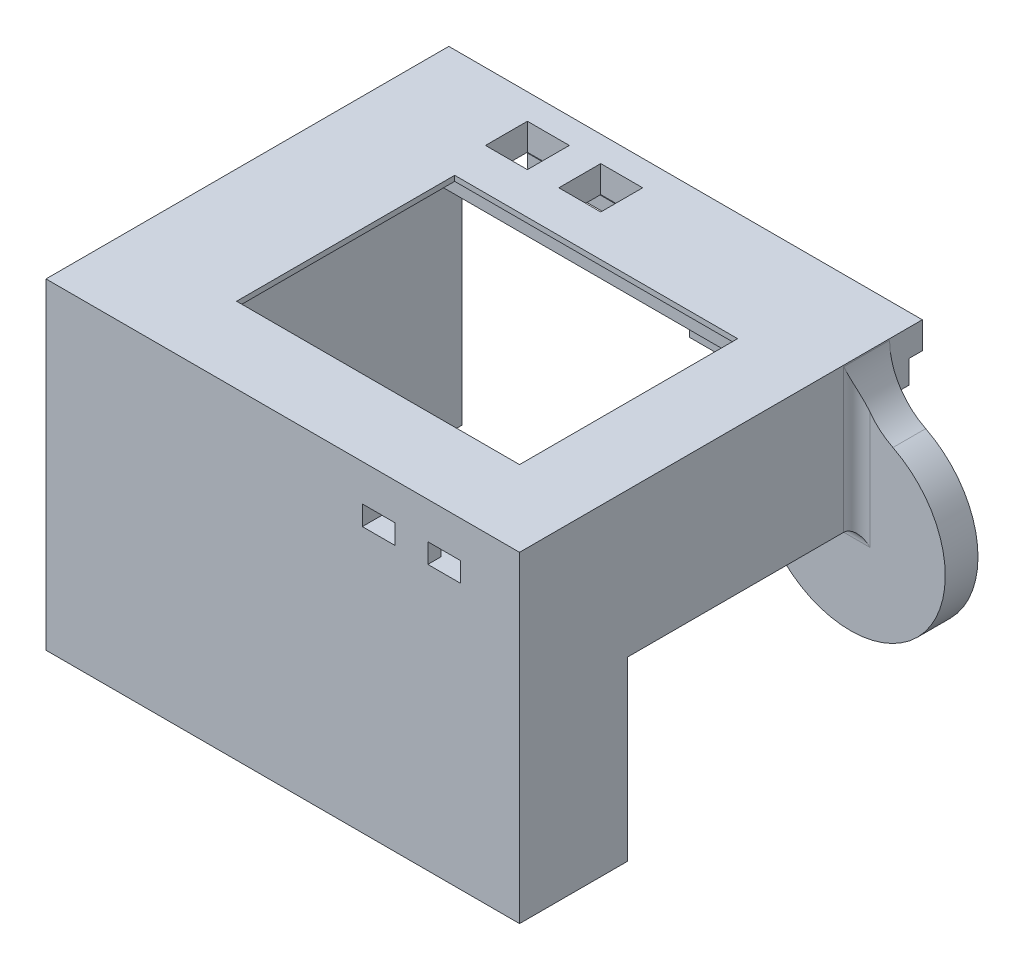
SolidWorks part; units mm, degrees
ref_plane "Front Plane" through (0, 0, 0) normal (0, 0, 1) x (1, 0, 0)
ref_plane "Top Plane" through (0, 0, 0) normal (0, 1, 0) x (1, 0, 0)
ref_plane "Right Plane" through (0, 0, 0) normal (1, 0, 0) x (0, 0, -1)
sketch "Sketch1" plane through (0, 0, 0) normal (0, 1, 0) x (1, 0, 0)
  line L0 (23.7457, 59.297) -> (23.7457, 2.797)
  line L1 (33.7457, 49.297) -> (86.0457, 49.297)
  line L2 (33.7457, 49.297) -> (33.7457, 12.797)
  line L3 (33.7457, 12.797) -> (86.0457, 12.797)
  line L4 (86.0457, 49.297) -> (86.0457, 12.797)
  line L5 (23.7457, 2.797) -> (96.0457, 2.797)
  line L6 (96.0457, 59.297) -> (96.0457, 2.797)
  line L7 (23.7457, 59.297) -> (96.0457, 59.297)
  dimension "D1" = 36.5
  dimension "D2" = 52.3
  dimension "D3" = 10
extrude "Boss-Extrude1" add sketch "Sketch1" along normal blind 3.3
sketch "Sketch2" plane through (0, 0, 0) normal (0, -1, 0) x (1, 0, 0)
  line L0 (96.0457, -2.797) -> (96.0457, -59.297) construction
  line L1 (23.7457, -2.797) -> (96.0457, -2.797)
  line L2 (23.7457, -2.797) -> (23.7457, -4.797)
  line L3 (23.7457, -4.797) -> (96.0457, -4.797)
  line L4 (96.0457, -2.797) -> (96.0457, -4.797)
  dimension "D1" = 2
extrude "Boss-Extrude2" add sketch "Sketch2" along normal blind 45
sketch "Sketch3" plane through (0, 0, -4.797) normal (0, 0, -1) x (-1, 0, 0)
  line L0 (-23.7457, -45) -> (-96.0457, -45) construction
  line L1 (-96.0457, 0) -> (-94.0457, 0)
  line L2 (-96.0457, 0) -> (-96.0457, -45)
  line L3 (-96.0457, -45) -> (-94.0457, -45)
  line L4 (-94.0457, 0) -> (-94.0457, -45)
  line L6 (-23.7457, 0) -> (-25.7457, 0)
  line L7 (-23.7457, 0) -> (-23.7457, -45)
  line L8 (-23.7457, -45) -> (-25.7457, -45)
  line L9 (-25.7457, 0) -> (-25.7457, -45)
  dimension "D1" = 2
  dimension "D2" = 2
extrude "Boss-Extrude3" add sketch "Sketch3" along normal up to surface (54.5 mm away) up to face at (59.8957, 1.65, -59.297)
sketch "Sketch5" plane through (0, 3.3, 0) normal (0, 1, 0) x (1, 0, 0)
  line L1 (23.7457, 59.297) -> (96.0457, 59.297)
  line L2 (23.7457, 59.297) -> (23.7457, 2.797)
  line L3 (23.7457, 2.797) -> (96.0457, 2.797)
  line L4 (96.0457, 59.297) -> (96.0457, 2.797)
  line L9 (41.2457, 47.697) -> (41.2457, 14.397)
  line L10 (41.2457, 47.697) -> (84.4457, 47.697)
  line L11 (84.4457, 47.697) -> (84.4457, 14.397)
  line L12 (84.4457, 14.397) -> (41.2457, 14.397)
  point P6 (34.2457, 48.797)
  point P7 (34.2457, 13.297)
  point P8 (85.5457, 13.297)
  point P9 (85.5457, 48.797)
  dimension "D2" = 11.6
  dimension "D1" = 17.5
  dimension "D3" = 11.6
  dimension "D4" = 11.6
extrude "Boss-Extrude6" add sketch "Sketch5" along normal blind 0.8
sketch "Sketch6" plane through (0, 0, -4.797) normal (0, 0, -1) x (-1, 0, 0)
  line L0 (-25.7457, 0) -> (-25.7457, -45) construction
  line L1 (-94.0457, 0) -> (-25.7457, 0)
  line L2 (-94.0457, 0) -> (-94.0457, -1.5)
  line L3 (-94.0457, -1.5) -> (-25.7457, -1.5)
  line L4 (-25.7457, 0) -> (-25.7457, -1.5)
  dimension "D1" = 1.5
extrude "Boss-Extrude7" add sketch "Sketch6" along normal blind 7.8
sketch "Sketch7" plane through (0, 0, -4.797) normal (0, 0, -1) x (-1, 0, 0)
  line L0 (-94.0457, -1.5) -> (-87.0457, -1.5) construction
  line L1 (-94.0457, -1.5) -> (-25.7457, -1.5) construction
  line L2 (-87.0457, -1.5) -> (-72.0457, -1.5) construction
  line L3 (-87.0457, -1.5) -> (-87.0457, -4.5)
  line L4 (-87.0457, -4.5) -> (-72.0457, -4.5)
  line L5 (-72.0457, -4.5) -> (-72.0457, -1.5)
  line L6 (-72.0457, -1.5) -> (-70.5457, -1.5)
  line L7 (-70.5457, -1.5) -> (-70.5457, -6)
  line L8 (-70.5457, -6) -> (-88.5457, -6)
  line L9 (-88.5457, -6) -> (-88.5457, -1.5)
  line L10 (-88.5457, -1.5) -> (-87.0457, -1.5)
  dimension "D1" = 7
  dimension "D2" = 15
  dimension "D3" = 3
  dimension "D4" = 1.5
  dimension "D5" = 1.5
  dimension "D6" = 1.5
extrude "Boss-Extrude8" add sketch "Sketch7" along normal up to surface (7.8 mm away) up to face at (59.8957, -0.75, -12.597)
sketch "Sketch8" plane through (0, 0, -59.297) normal (0, 0, -1) x (-1, 0, 0)
  line L0 (-94.0457, 0) -> (-25.7457, 0) construction
  line L1 (-88.5457, -6) -> (-70.503, -6)
  line L2 (-88.5457, -6) -> (-88.5457, 0)
  line L3 (-88.5457, 0) -> (-70.503, 0)
  line L4 (-70.503, -6) -> (-70.503, 0)
  line L6 (-87.0457, -1.5) -> (-72.0457, -1.5)
  line L7 (-87.0457, -1.5) -> (-87.0457, -4.5)
  line L8 (-87.0457, -4.5) -> (-72.0457, -4.5)
  line L9 (-72.0457, -1.5) -> (-72.0457, -4.5)
extrude "Boss-Extrude9" add sketch "Sketch8" against normal up to surface (10 mm away) up to face at (59.8957, 1.65, -49.297)
sketch "Sketch9" plane through (0, 0, 0) normal (0, -1, 0) x (1, 0, 0)
  line L0 (86.0457, -49.297) -> (86.0457, -44.297) construction
  line L1 (86.0457, -12.797) -> (86.0457, -49.297) construction
  line L2 (86.0457, -44.297) -> (90.0457, -44.297)
  line L3 (90.0457, -44.297) -> (90.0457, -17.797)
  line L4 (90.0457, -17.797) -> (86.0457, -17.797)
  line L5 (86.0457, -17.797) -> (86.0457, -12.797) construction
  line L6 (86.0457, -44.297) -> (86.0457, -17.797)
  dimension "D1" = 5
  dimension "D2" = 5
  dimension "D3" = 4
extrude "Cut-Extrude1" cut sketch "Sketch9" against normal blind 2
sketch "Sketch10" plane through (0, 0, -59.297) normal (0, 0, -1) x (-1, 0, 0)
  line L0 (-94.0457, 0) -> (-94.0457, -45) construction
  line L1 (-96.0457, -45) -> (-94.0457, -45)
  line L2 (-96.0457, -45) -> (-96.0457, -15)
  line L3 (-96.0457, -15) -> (-94.0457, -15)
  line L4 (-94.0457, -45) -> (-94.0457, -15)
  dimension "D1" = 30
extrude "Cut-Extrude2" cut sketch "Sketch10" against normal blind 40
sketch "Sketch11" plane through (0, -1.5, 0) normal (0, -1, 0) x (1, 0, 0)
  line L0 (94.0457, -4.797) -> (94.0457, -7.197) construction
  line L1 (94.0457, -4.797) -> (88.5457, -4.797) construction
  line L2 (94.0457, -12.597) -> (94.0457, -4.797) construction
  line L3 (94.0457, -7.197) -> (94.0457, -8.197)
  line L4 (94.0457, -8.197) -> (92.0457, -8.197)
  line L5 (92.0457, -8.197) -> (92.0457, -7.197)
  line L6 (92.0457, -7.197) -> (94.0457, -7.197)
  line L7 (25.7457, -7.197) -> (27.7457, -7.197)
  line L8 (25.7457, -12.597) -> (25.7457, -4.797) construction
  line L9 (27.7457, -7.197) -> (27.7457, -8.197)
  line L10 (27.7457, -8.197) -> (25.7457, -8.197)
  line L11 (25.7457, -8.197) -> (25.7457, -7.197)
  line L12 (70.5457, -4.797) -> (25.7457, -4.797) construction
  dimension "D1" = 2.4
  dimension "D2" = 2
  dimension "D3" = 1
  dimension "D4" = 2.4
  dimension "D5" = 1
  dimension "D6" = 2
extrude "Boss-Extrude10" add sketch "Sketch11" along normal blind 20
sketch "Sketch13" plane through (0, 0, -59.297) normal (0, 0, -1) x (-1, 0, 0)
  line L13 (-87.0457, -1.5) -> (-72.0457, -1.5)
  line L14 (-87.0457, -1.5) -> (-87.0457, -4.5)
  line L15 (-87.0457, -4.5) -> (-72.0457, -4.5)
  line L16 (-72.0457, -1.5) -> (-72.0457, -4.5)
  line L24 (-96.0457, 4.1) -> (-96.0457, -15)
  line L25 (-96.0457, -15) -> (-94.0457, -15)
  line L26 (-94.0457, -15) -> (-94.0457, 0)
  line L27 (-94.0457, 0) -> (-88.5457, 0)
  line L28 (-88.5457, 0) -> (-88.5457, -6)
  line L29 (-88.5457, -6) -> (-70.503, -6)
  line L30 (-70.503, -6) -> (-70.503, 0)
  line L31 (-70.503, 0) -> (-25.7457, 0)
  line L32 (-25.7457, 0) -> (-25.7457, -45)
  line L33 (-25.7457, -45) -> (-23.7457, -45)
  line L34 (-23.7457, -45) -> (-23.7457, 4.1)
  line L35 (-23.7457, 4.1) -> (-96.0457, 4.1)
  line L36 (-96.0457, 4.1) -> (-96.0457, -15)
  line L37 (-96.0457, -15) -> (-94.0457, -15)
  line L38 (-94.0457, -15) -> (-94.0457, 0)
  line L39 (-94.0457, 0) -> (-88.5457, 0)
  line L40 (-88.5457, 0) -> (-88.5457, -6)
  line L41 (-88.5457, -6) -> (-70.503, -6)
  line L42 (-70.503, -6) -> (-70.503, 0)
  line L43 (-70.503, 0) -> (-25.7457, 0)
  line L44 (-25.7457, 0) -> (-25.7457, -45)
  line L45 (-25.7457, -45) -> (-23.7457, -45)
  line L46 (-23.7457, -45) -> (-23.7457, 4.1)
  line L47 (-23.7457, 4.1) -> (-96.0457, 4.1)
  dimension "D1" = 0
extrude "Boss-Extrude11" add sketch "Sketch13" along normal blind 5
sketch "Sketch12" plane through (0, 4.1, 0) normal (0, 1, 0) x (1, 0, 0)
  line L0 (23.7457, 60.297) -> (39.7457, 60.297) construction
  line L1 (23.7457, 64.297) -> (23.7457, 2.797) construction
  line L2 (39.7457, 60.297) -> (39.7457, 64.297) construction
  line L4 (45.9457, 60.297) -> (50.9457, 60.297) construction
  line L5 (39.7457, 60.297) -> (45.9457, 60.297)
  line L6 (39.7457, 60.297) -> (39.7457, 54.097)
  line L7 (39.7457, 54.097) -> (45.9457, 54.097)
  line L8 (45.9457, 60.297) -> (45.9457, 54.097)
  line L10 (50.9457, 60.297) -> (57.1457, 60.297)
  line L11 (50.9457, 60.297) -> (50.9457, 54.097)
  line L12 (50.9457, 54.097) -> (57.1457, 54.097)
  line L13 (57.1457, 60.297) -> (57.1457, 54.097)
  line L14 (23.7457, 64.297) -> (96.0457, 64.297) construction
  dimension "D1" = 4
  dimension "D2" = 16
  dimension "D3" = 6.2
  dimension "D4" = 6.2
  dimension "D5" = 5
  dimension "D6" = 6.2
  dimension "D7" = 6.2
extrude "Cut-Extrude3" cut sketch "Sketch12" against normal blind 10
sketch "Sketch14" plane through (0, 0, 0) normal (0, -1, 0) x (1, 0, 0)
  line L0 (88.5457, -49.297) -> (88.5457, -64.297) construction
  line L1 (70.503, -49.297) -> (88.5457, -49.297)
  line L2 (70.503, -49.297) -> (70.503, -54.297)
  line L3 (70.503, -54.297) -> (88.5457, -54.297)
  line L4 (88.5457, -49.297) -> (88.5457, -54.297)
  dimension "D1" = 5
extrude "Cut-Extrude4" cut sketch "Sketch14" along normal blind 25
sketch "Sketch15" plane through (0, 0, -64.297) normal (0, 0, -1) x (-1, 0, 0)
  line L1 (-100.1161, -15.1013) -> (-70.503, -15.1013)
  line L2 (-100.1161, -15.1013) -> (-100.1161, 0)
  line L3 (-100.1161, 0) -> (-70.503, 0)
  line L4 (-70.503, -15.1013) -> (-70.503, 0)
extrude "Cut-Extrude5" cut sketch "Sketch15" against normal blind 2
sketch "Sketch17" plane through (0, 0, 0) normal (0, -1, 0) x (1, 0, 0)
  line L1 (88.5457, -54.297) -> (94.0457, -54.297)
  line L2 (88.5457, -54.297) -> (88.5457, -62.297)
  line L3 (88.5457, -62.297) -> (94.0457, -62.297)
  line L4 (94.0457, -54.297) -> (94.0457, -62.297)
extrude "Boss-Extrude12" add sketch "Sketch17" along normal up to surface (6 mm away) up to face at (79.5244, -6, -58.297)
sketch "Sketch20" plane through (0, 0, -19.297) normal (0, 0, -1) x (-1, 0, 0)
  line L0 (-94.0457, -21.5) -> (-94.0457, -1.5) construction
  line L1 (-96.0457, -15) -> (-94.0457, -15)
  line L2 (-96.0457, -15) -> (-96.0457, -18)
  line L3 (-96.0457, -18) -> (-94.0457, -18)
  line L4 (-94.0457, -15) -> (-94.0457, -18)
  dimension "D1" = 3
extrude "Boss-Extrude14" add sketch "Sketch20" along normal up to surface (43 mm away) up to face at (86.8648, -7, -62.297)
sketch "Sketch21" plane through (0, 0, -62.297) normal (0, 0, -1) x (-1, 0, 0)
  line L0 (-96.0457, -18) -> (-94.0457, -18) construction
  circle A0 centre (-95.0457, -18) radius 14.5
  dimension "D1" = 29
extrude "Boss-Extrude15" add sketch "Sketch21" against normal blind 8
sketch "Sketch22" plane through (0, 0, -62.297) normal (0, 0, -1) x (-1, 0, 0)
  circle A0 centre (-95.0457, -18) radius 12.75
  dimension "D1" = 25.5
extrude "Cut-Extrude6" cut sketch "Sketch22" against normal blind 6
fillet "Fillet1" radius 2 3 edges at (96.0457, -10.7673, -54.297) (95.0457, -18, -54.297) (94.0457, -9, -54.297)
sketch "Sketch23" plane through (0, 0, 0) normal (0, -1, 0) x (1, 0, 0)
  line L1 (39.7457, -54.097) -> (57.154, -54.097)
  line L2 (39.7457, -54.097) -> (39.7457, -53.097)
  line L3 (39.7457, -53.097) -> (57.154, -53.097)
  line L4 (57.154, -54.097) -> (57.154, -53.097)
  dimension "D1" = 1
extrude "Boss-Extrude16" add sketch "Sketch23" along normal blind 2
sketch "Sketch24" plane through (0, 0, -54.097) normal (0, 0, -1) x (-1, 0, 0)
  line L0 (-57.154, -2) -> (-54.754, -2) construction
  line L1 (-39.7457, -2) -> (-57.154, -2) construction
  line L2 (-54.754, -2) -> (-53.3457, -2)
  line L3 (-53.3457, -2) -> (-50.9457, -2) construction
  line L4 (-48.4457, 0) -> (-48.4457, -7.5732) construction
  line L5 (-45.9457, 0) -> (-50.9457, 0) construction
  line L6 (-50.9457, 0) -> (-50.9457, -2) construction
  line L7 (-53.3457, -2) -> (-53.3457, 0)
  line L8 (-53.3457, 0) -> (-54.754, 0)
  line L9 (-54.754, 0) -> (-54.754, -2)
  line L10 (-43.5457, 0) -> (-42.1374, 0)
  line L11 (-43.5457, -2) -> (-43.5457, 0)
  line L12 (-42.1374, -2) -> (-43.5457, -2)
  line L13 (-42.1374, 0) -> (-42.1374, -2)
  point P18 (0, 0)
  point P20 (-46.9912, -2)
  point P21 (-50.9457, -2)
  dimension "D1" = 2.4
  dimension "D3" = 2.4
extrude "Boss-Extrude17" add sketch "Sketch24" along normal up to surface (8.2 mm away) up to face at (82.2957, -18, -62.297)
sketch "Sketch25" plane through (0, 0, 0) normal (0, -1, 0) x (1, 0, 0)
  line L0 (39.7457, -60.297) -> (57.1457, -60.297)
  line L5 (42.9587, -60.297) -> (42.9587, -62.297) construction
  line L6 (54.754, -62.297) -> (53.3457, -62.297) construction
  line L7 (57.1457, -60.297) -> (57.1457, -62.297)
  line L8 (57.1457, -62.297) -> (39.7457, -62.297)
  line L9 (39.7457, -62.297) -> (39.7457, -60.297)
extrude "Boss-Extrude18" add sketch "Sketch25" along normal blind 2
sketch "Sketch26" plane through (0, 4.1, 0) normal (0, 1, 0) x (1, 0, 0)
  line L23 (39.6457, 53.997) -> (46.0457, 53.997)
  line L24 (39.6457, 60.397) -> (39.6457, 53.997)
  line L25 (46.0457, 60.397) -> (39.6457, 60.397)
  line L26 (46.0457, 53.997) -> (46.0457, 60.397)
  line L27 (39.6457, 53.997) -> (46.0457, 53.997)
  line L28 (39.6457, 60.397) -> (39.6457, 53.997)
  line L29 (46.0457, 60.397) -> (39.6457, 60.397)
  line L30 (46.0457, 53.997) -> (46.0457, 60.397)
  line L41 (50.8457, 53.997) -> (57.2457, 53.997)
  line L42 (57.2457, 53.997) -> (57.2457, 60.397)
  line L43 (57.2457, 60.397) -> (50.8457, 60.397)
  line L44 (50.8457, 60.397) -> (50.8457, 53.997)
  line L45 (50.8457, 53.997) -> (57.2457, 53.997)
  line L46 (57.2457, 53.997) -> (57.2457, 60.397)
  line L47 (57.2457, 60.397) -> (50.8457, 60.397)
  line L48 (50.8457, 60.397) -> (50.8457, 53.997)
  dimension "D1" = 0.1
  dimension "D2" = 0.1
extrude "Cut-Extrude7" cut sketch "Sketch26" against normal up to surface (4.1 mm away) up to face at (73.9707, 0, -31.047)
sketch "Sketch28" plane through (0, 0, -4.797) normal (0, 0, -1) x (-1, 0, 0)
  line L0 (-87.0457, -4.5) -> (-72.0457, -4.5) construction
  line L1 (-87.0457, -1.5) -> (-82.0457, -1.5)
  line L2 (-87.0457, -1.5) -> (-87.0457, -4.5)
  line L3 (-87.0457, -4.5) -> (-82.0457, -4.5)
  line L4 (-82.0457, -1.5) -> (-82.0457, -4.5)
  line L5 (-82.0457, -1.5) -> (-77.0457, -1.5) construction
  line L6 (-72.0457, -1.5) -> (-77.0457, -1.5)
  line L7 (-72.0457, -1.5) -> (-72.0457, -4.5)
  line L8 (-72.0457, -4.5) -> (-77.0457, -4.5)
  line L9 (-77.0457, -1.5) -> (-77.0457, -4.5)
  dimension "D1" = 5
  dimension "D2" = 5
extrude "Cut-Extrude9" cut sketch "Sketch28" against normal up to surface (2 mm away) up to face at (59.8957, -20.45, -2.797)
sketch "Sketch29" plane through (0, 0, -62.297) normal (0, 0, -1) x (-1, 0, 0)
  circle A0 centre (-95.0457, -18) radius 14.5
  circle A1 centre (-95.0457, -18) radius 12.75
extrude "Cut-Extrude10" cut sketch "Sketch29" against normal blind 3
fillet "Fillet2" radius 10 1 edges at (96.0457, -3.5345, -55.797)
